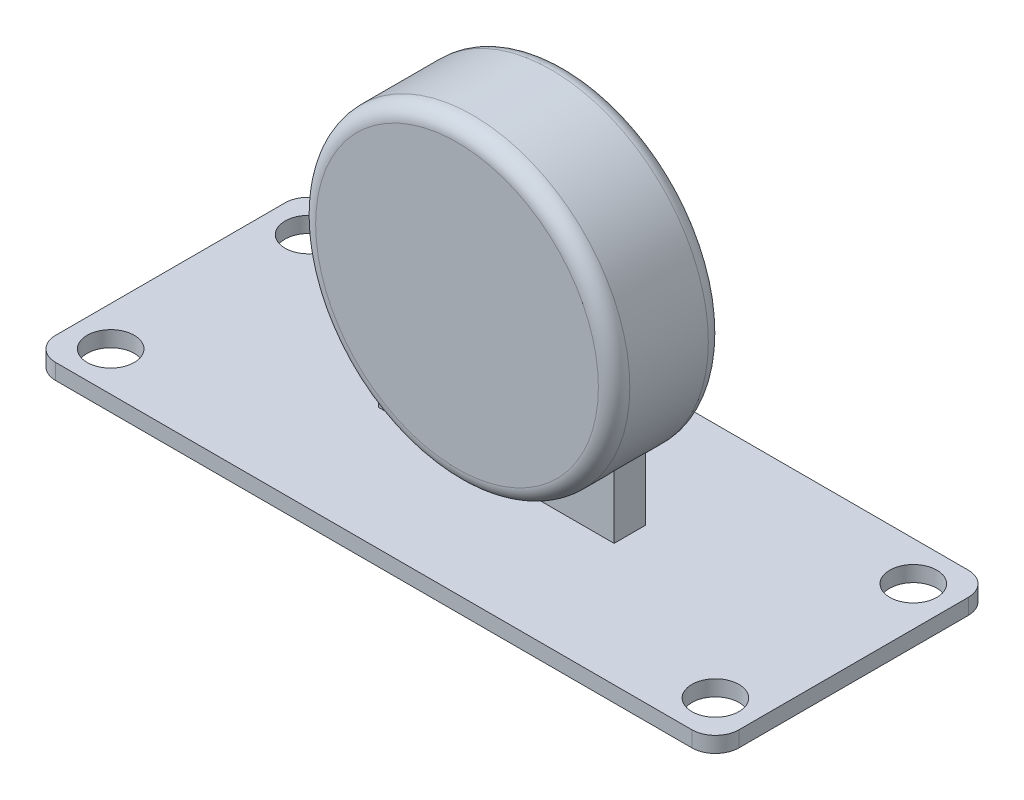
SolidWorks part; units mm, degrees
ref_plane "Front Plane" through (0, 0, 0) normal (0, 0, 1) x (1, 0, 0)
ref_plane "Top Plane" through (0, 0, 0) normal (0, 1, 0) x (1, 0, 0)
ref_plane "Right Plane" through (0, 0, 0) normal (1, 0, 0) x (0, 0, -1)
sketch "Sketch1" plane through (0, 0, 0) normal (0, 1, 0) x (1, 0, 0)
  line L0 (-514.35, 223.52) -> (514.35, 223.52)
  line L1 (-488.95, -160.02) -> (488.95, -160.02) construction
  line L2 (-488.95, 160.02) -> (-488.95, -160.02) construction
  line L3 (488.95, 160.02) -> (-488.95, 160.02) construction
  line L4 (488.95, -160.02) -> (488.95, 160.02) construction
  line L5 (-488.95, -160.02) -> (488.95, 160.02) construction
  line L6 (-488.95, 160.02) -> (488.95, -160.02) construction
  line L7 (552.45, -185.42) -> (552.45, 185.42)
  line L8 (-514.35, -223.52) -> (514.35, -223.52)
  line L9 (-552.45, -185.42) -> (-552.45, 185.42)
  circle A0 centre (-488.95, 160.02) radius 38.1
  circle A1 centre (488.95, 160.02) radius 38.1
  circle A2 centre (488.95, -160.02) radius 38.1
  circle A3 centre (-488.95, -160.02) radius 38.1
  arc A4 (-514.35, -223.52) -> (-552.45, -185.42) centre (-514.35, -185.42) cw
  arc A5 (552.45, -185.42) -> (514.35, -223.52) centre (514.35, -185.42) cw
  arc A6 (514.35, 223.52) -> (552.45, 185.42) centre (514.35, 185.42) cw
  arc A7 (-514.35, 223.52) -> (-552.45, 185.42) centre (-514.35, 185.42) ccw
  point P0 (0, 0)
  dimension "D3" = 63.5
  dimension "D7" = 38.1
  dimension "D1" = 977.9
  dimension "D2" = 320.04
  dimension "D4" = 63.5
  dimension "D5" = 63.5
  dimension "D6" = 63.5
extrude "Boss-Extrude1" add sketch "Sketch1" along normal blind 25.4
sketch "Sketch3" plane through (0, 0, 0) normal (0, 0, 1) x (1, 0, 0)
  line L0 (0, 0) -> (0, 255.3098) construction
  line L1 (-190.5, 25.4) -> (190.5, 25.4)
  line L3 (-514.35, 25.4) -> (514.35, 25.4) construction
  line L4 (-190.5, 25.4) -> (-190.5, 127)
  line L5 (190.5, 25.4) -> (190.5, 127)
  arc A0 (-190.5, 127) -> (190.5, 127) centre (0, 295.0052) ccw
  point P4 (0, 25.4)
  dimension "D1" = 381
  dimension "D4" = 101.6
  dimension "D3" = 254
  dimension "D2" = 101.6
extrude "Boss-Extrude2" add sketch "Sketch3" along normal blind 25.4 and the other way blind 25.4
sketch "Sketch4" plane through (0, 0, 0) normal (0, 0, 1) x (1, 0, 0)
  line L0 (0, 295.0052) -> (0, 0) construction
  circle A0 centre (0, 295.0052) radius 254
  arc A4 (-190.5, 127) -> (190.5, 127) centre (0, 295.0052) ccw construction
  dimension "D1" = 508
extrude "Boss-Extrude3" add sketch "Sketch4" along normal blind 88.9 and the other way blind 88.9
fillet "Fillet1" radius 25.4 2 edges at (254, 295.0052, -88.9) (254, 295.0052, 88.9)
